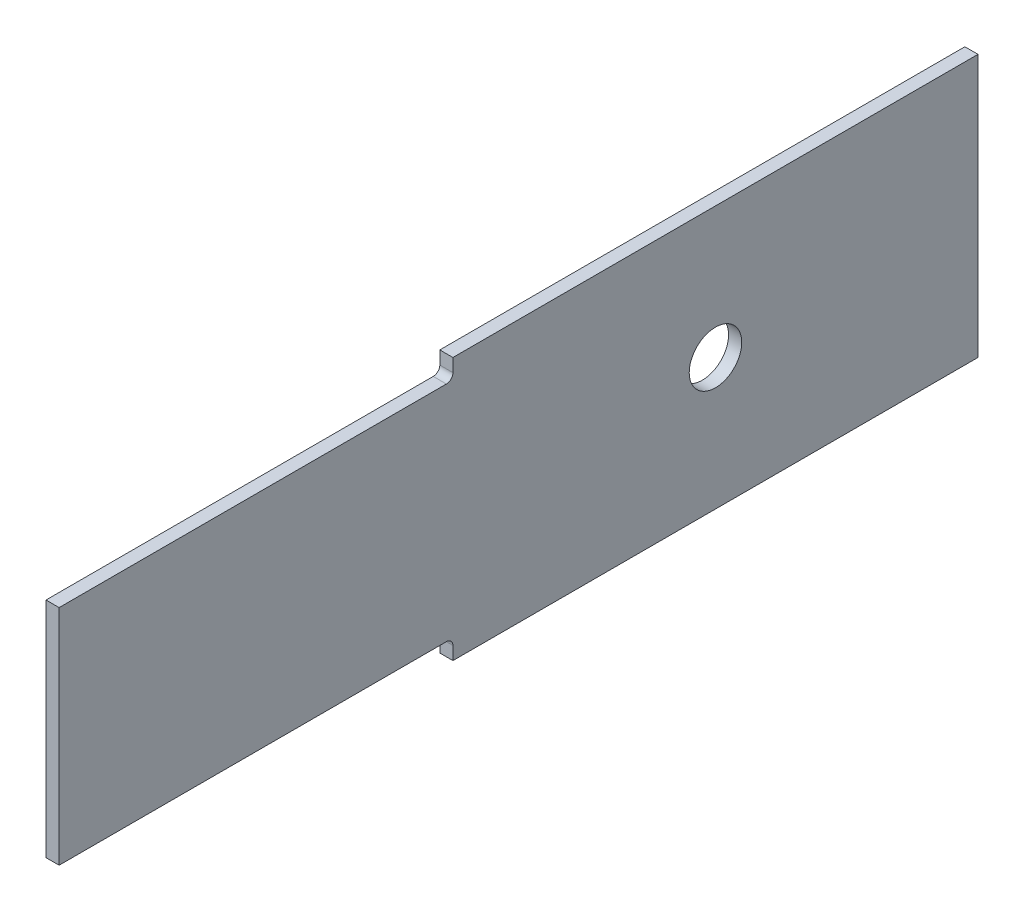
SolidWorks part; units mm, degrees
ref_plane "Front Plane" through (0, 0, 0) normal (0, 0, 1) x (1, 0, 0)
ref_plane "Top Plane" through (0, 0, 0) normal (0, 1, 0) x (1, 0, 0)
ref_plane "Right Plane" through (0, 0, 0) normal (1, 0, 0) x (0, 0, -1)
sketch "Sketch1" plane through (0, 0, 0) normal (0, 0, 1) x (1, 0, 0)
  line L1 (-1, -20) -> (1, -20)
  line L2 (-1, -20) -> (-1, 20)
  line L3 (-1, 20) -> (1, 20)
  line L4 (1, -20) -> (1, 20)
  line L5 (-1, -20) -> (1, 20) construction
  line L6 (-1, 20) -> (1, -20) construction
  point P0 (0, 0)
  dimension "D1" = 2
  dimension "D2" = 40
extrude "Boss-Extrude1" add sketch "Sketch1" along normal blind 80
sketch "Sketch2" plane through (0, 0, 80) normal (0, 0, 1) x (1, 0, 0)
  line L0 (1, -20) -> (1, 20) construction
  line L1 (-1, -17) -> (1, -17)
  line L2 (-1, -17) -> (-1, 17)
  line L3 (-1, 17) -> (1, 17)
  line L4 (1, -17) -> (1, 17)
  line L5 (-1, -17) -> (1, 17) construction
  line L6 (-1, 17) -> (1, -17) construction
  point P0 (0, 0)
  dimension "D1" = 34
extrude "Boss-Extrude2" add sketch "Sketch2" along normal blind 60
fillet "Fillet1" radius 1 2 edges at (0, -17, 80) (0, 17, 80)
sketch "Sketch3" plane through (-1, 0, 0) normal (-1, 0, 0) x (0, 0, 1)
  circle A0 centre (40, 0) radius 2
  dimension "D1" = 4
extrude "Cut-Extrude1" cut sketch "Sketch3" against normal through all
sketch "Sketch4" plane through (-1, 0, 0) normal (-1, 0, 0) x (0, 0, 1)
  circle A0 centre (40, 0) radius 4
  dimension "D1" = 8
extrude "Cut-Extrude2" cut sketch "Sketch4" against normal through all
